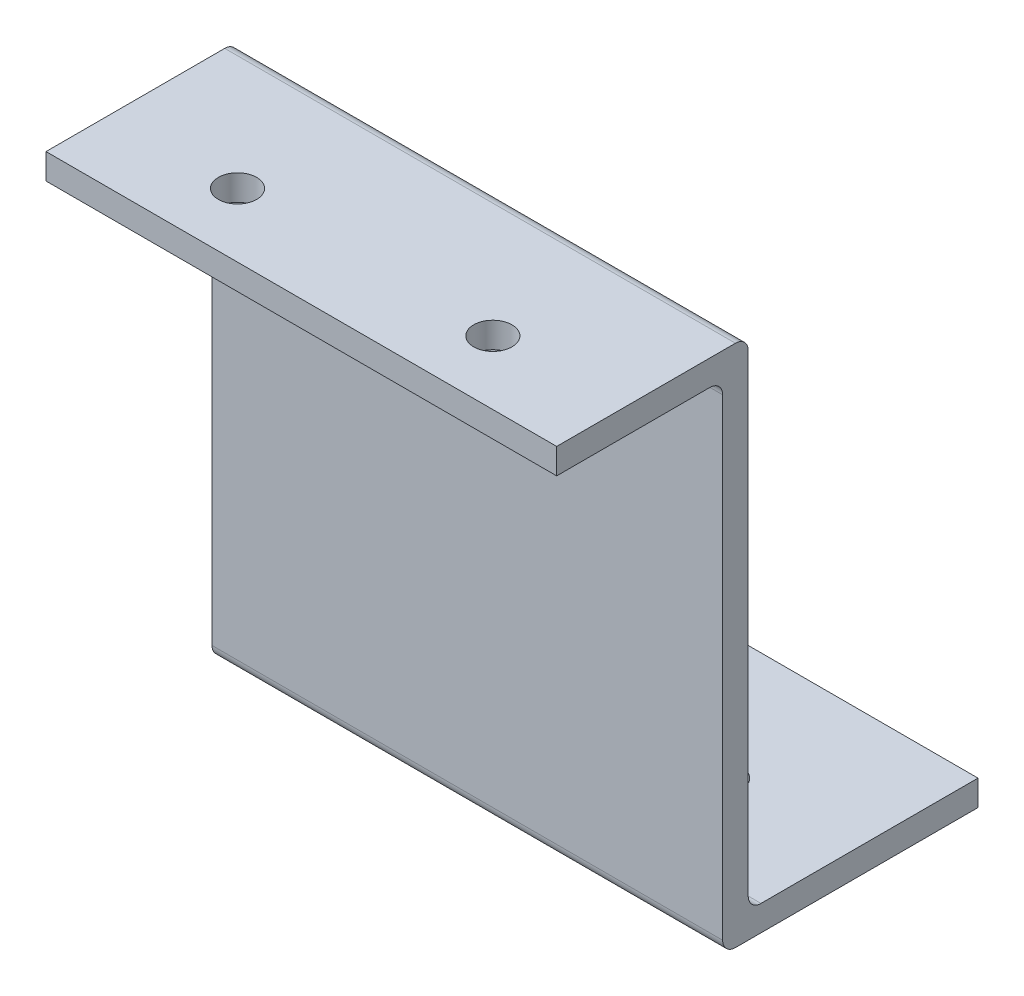
SolidWorks part; units mm, degrees
ref_plane "Front Plane" through (0, 0, 0) normal (0, 0, 1) x (1, 0, 0)
ref_plane "Top Plane" through (0, 0, 0) normal (0, 1, 0) x (1, 0, 0)
ref_plane "Right Plane" through (0, 0, 0) normal (1, 0, 0) x (0, 0, -1)
sketch "Sketch1" plane through (0, 0, 0) normal (1, 0, 0) x (0, 0, -1)
  line L1 (0, 0) -> (15, 0)
  line L2 (0, 0) -> (0, 2)
  line L3 (0, 2) -> (15, 2)
  line L4 (15, 0) -> (15, 2)
  line L5 (15, 2) -> (13, 2)
  line L6 (15, 2) -> (15, -39)
  line L7 (15, -39) -> (13, -39)
  line L8 (13, 2) -> (13, -39)
  line L9 (13, -39) -> (33, -39)
  line L10 (13, -39) -> (13, -37)
  line L11 (13, -37) -> (33, -37)
  line L12 (33, -39) -> (33, -37)
  dimension "D1" = 2
  dimension "D2" = 15
  dimension "D3" = 2
  dimension "D4" = 41
  dimension "D5" = 2
  dimension "D6" = 20
extrude "Boss-Extrude1" add sketch "Sketch1" along normal blind 40 contours L8 L3 L2 L1 | L3 L8 L1 L4 | L8 L11 L6 L1 | L9 L12 L11 L6 | L11 L8 L7 L6
sketch "Sketch2" plane through (0, 2, 0) normal (0, 1, 0) x (1, 0, 0)
  line L1 (0, 0) -> (0, 15) construction
  line L2 (40, 0) -> (40, 15) construction
  line L3 (40, 15) -> (0, 15) construction
  circle A0 centre (10, 5) radius 1.5
  circle A1 centre (30, 5) radius 1.5
  dimension "D1" = 10
  dimension "D3" = 10
  dimension "D4" = 10
  dimension "D2" = 10
extrude "Cut-Extrude1" cut sketch "Sketch2" against normal blind 40
fillet "Fillet1" radius 1 4 edges at (20, 0, -13) (20, 2, -15) (20, -39, -13) (20, -37, -15)
ref_plane "Plane1" through (40, -37, -33) normal (0, 0, -1) x (-1, 0, 0)
sketch "Sketch4" plane through (0, -37, 0) normal (0, 1, 0) x (1, 0, 0)
  line L0 (40, 16) -> (40, 33) construction
  line L1 (40, 33) -> (0, 33) construction
  line L2 (0, 16) -> (0, 33) construction
  circle A0 centre (30, 23) radius 1.5
  circle A1 centre (10, 23) radius 1.5
  dimension "D1" = 10
  dimension "D2" = 10
  dimension "D3" = 10
  dimension "D4" = 10
extrude "Cut-Extrude2" cut sketch "Sketch4" against normal blind 40
